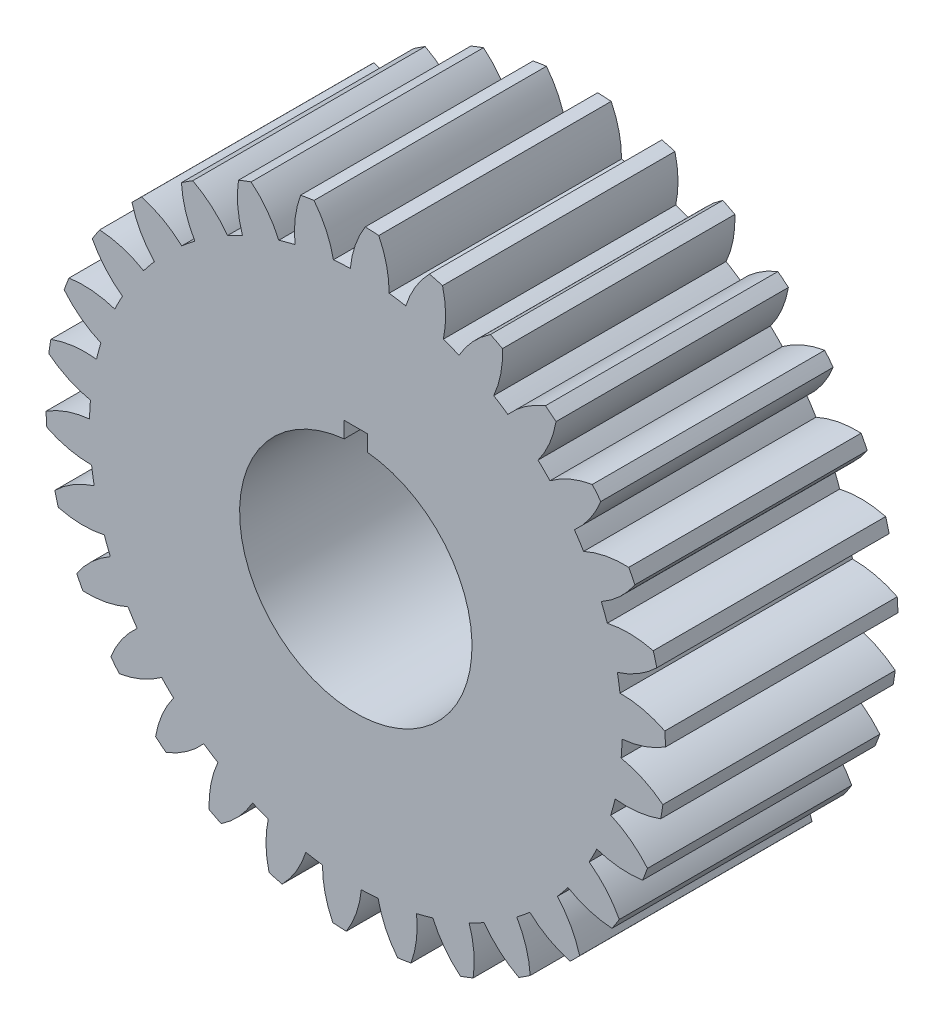
SolidWorks part; units mm, degrees
ref_plane "前视基准面" through (0, 0, 0) normal (0, 0, 1) x (1, 0, 0)
ref_plane "上视基准面" through (0, 0, 0) normal (0, 1, 0) x (1, 0, 0)
ref_plane "右视基准面" through (0, 0, 0) normal (1, 0, 0) x (0, 0, -1)
other "Configuration Table"
sketch "草图1" plane through (0, 0, 0) normal (0, 0, 1) x (1, 0, 0)
  circle A0 centre (0, 0) radius 34.375
  dimension "D1" = 68.75
extrude "凸台-拉伸1" add sketch "草图1" along normal blind 30
sketch "草图2" plane through (0, 0, 30) normal (0, 0, 1) x (1, 0, 0)
  line L0 (0, 0) -> (0, 50.1997) construction
  line L1 (2.5993, 49.5977) -> (0, 0) construction
  line L2 (0, 0) -> (18.1847, 49.9621) construction
  line L3 (0, 37.5) -> (12.0523, 33.1133) construction
  circle A0 centre (0, 0) radius 37.5 construction
  arc A2 (2.9655, 39.8899) -> (1.2204, 39.9814) centre (0, 0) ccw
  circle A3 centre (0, 0) radius 34.375 construction
  arc A4 (4.3005, 34.1049) -> (-0.712, 34.3676) centre (0, 0) ccw
  arc A5 (1.2204, 39.9814) -> (-0.712, 34.3676) centre (12.0523, 33.1133) ccw
  arc A6 (2.9655, 39.8899) -> (4.3005, 34.1049) centre (-8.525, 34.1917) cw
  dimension "D1" = 80
  dimension "D2" = 75
  dimension "D3" = 3
  dimension "D4" = 20
extrude "凸台-拉伸2" add sketch "草图2" against normal blind 30
pattern_circular "阵列(圆周)1" count 30 over 360 about axis through (0, 0, 0) along (0, 0, 1) of "凸台-拉伸2"
sketch "草图3" plane through (0, 0, 30) normal (0, 0, 1) x (1, 0, 0)
  line L1 (-1.5, 0) -> (1.5, 0)
  line L2 (-1.5, 0) -> (-1.5, 17)
  line L3 (-1.5, 17) -> (1.5, 17)
  line L4 (1.5, 0) -> (1.5, 17)
  circle A0 centre (0, 0) radius 15
  point P7 (0, 0)
  dimension "D1" = 30
  dimension "D2" = 3
  dimension "D3" = 17
extrude "切除-拉伸1" cut sketch "草图3" against normal blind 30 contours L2 A0 L4 L1 | L4 A0 L2 L1 | A0 L4 L3 L2
